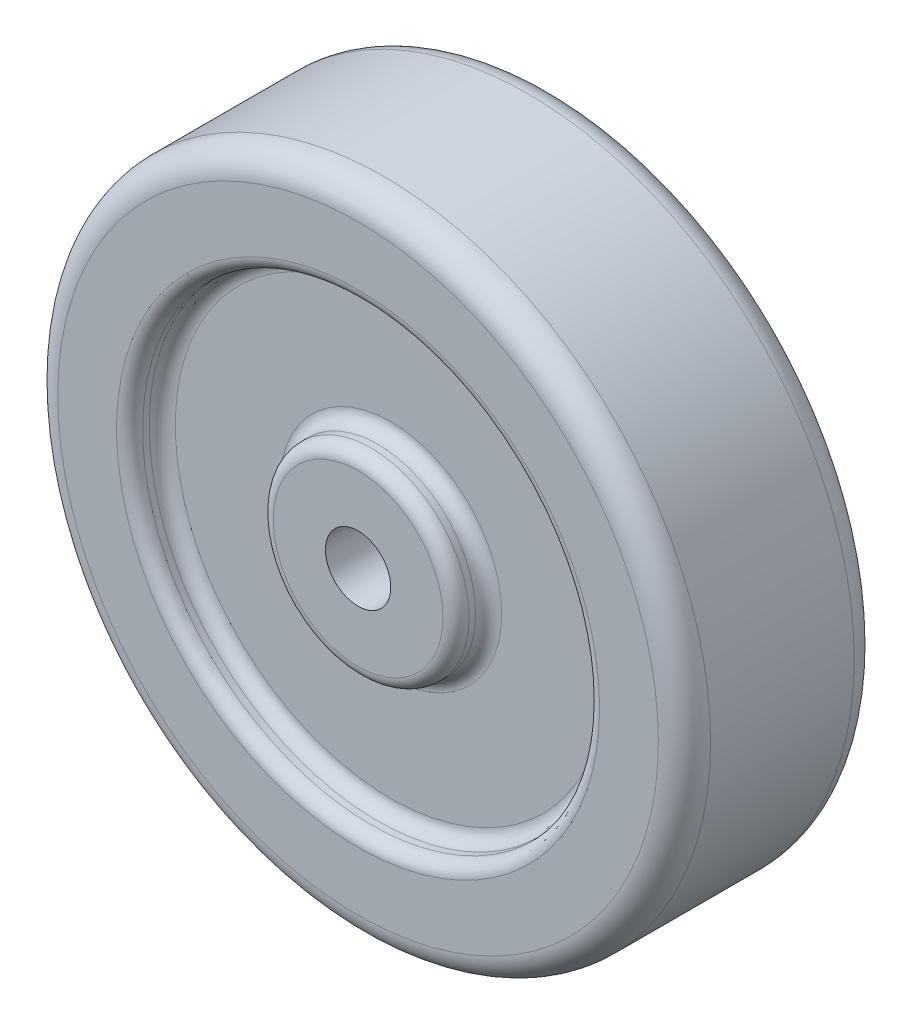
SolidWorks part; units mm, degrees
material "CA"
ref_plane "Front" through (0, 0, 0) normal (0, 0, 1) x (1, 0, 0)
ref_plane "Top" through (0, 0, 0) normal (0, 1, 0) x (1, 0, 0)
ref_plane "Right" through (0, 0, 0) normal (1, 0, 0) x (0, 0, -1)
sketch "Sketch1" plane through (0, 0, 0) normal (0, 0, 1) x (1, 0, 0)
  circle A0 centre (0, 0) radius 31.75
  dimension "D1" = 63.5
extrude "Boss-Extrude1" add sketch "Sketch1" along normal blind 9.525
fillet "Fillet1" radius 2.54 1 edges at (31.75, 0, 9.525)
sketch "Sketch2" plane through (0, 0, 9.525) normal (0, 0, 1) x (1, 0, 0)
  circle A0 centre (0, 0) radius 9.525
  circle A1 centre (0, 0) radius 22.225
  dimension "D1" = 19.05
  dimension "D2" = 44.45
extrude "Cut-Extrude1" cut sketch "Sketch2" against normal blind 3.175
fillet "Fillet2" radius 1.27 4 edges at (9.525, 0, 6.35) (9.525, 0, 9.525) (22.225, 0, 6.35) (22.225, 0, 9.525)
mirror "Mirror8" about plane through (0, 0, 0) normal (0, 0, 1) of bodies 102
sketch "Sketch3" plane through (0, 0, 9.525) normal (0, 0, 1) x (1, 0, 0)
  circle A0 centre (0, 0) radius 3.175
  dimension "D1" = 6.35
extrude "Cut-Extrude2" cut sketch "Sketch3" against normal through all
